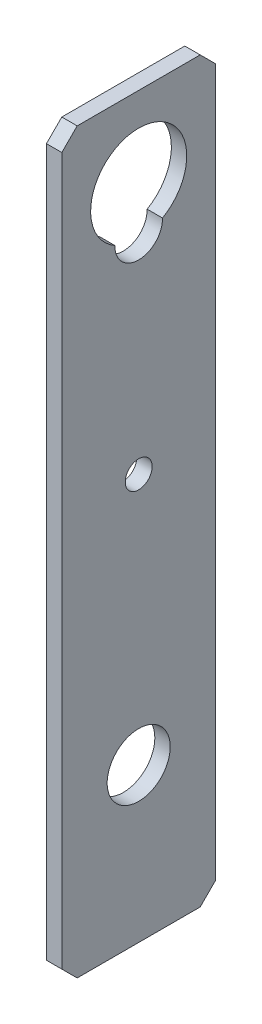
SolidWorks part; units mm, degrees
ref_plane "Front Plane" through (0, 0, 0) normal (0, 0, 1) x (1, 0, 0)
ref_plane "Top Plane" through (0, 0, 0) normal (0, 1, 0) x (1, 0, 0)
ref_plane "Right Plane" through (0, 0, 0) normal (1, 0, 0) x (0, 0, -1)
sketch "Sketch1" plane through (0, 0, 0) normal (1, 0, 0) x (0, 0, -1)
  line L1 (-10, -48) -> (10, -48)
  line L2 (-10, -48) -> (-10, 48)
  line L3 (-10, 48) -> (10, 48)
  line L4 (10, -48) -> (10, 48)
  line L5 (-10, -48) -> (10, 48) construction
  line L6 (-10, 48) -> (10, -48) construction
  point P0 (0, 0)
  dimension "D1" = 96
  dimension "D2" = 20
extrude "Boss-Extrude2" add sketch "Sketch1" along normal blind 2
sketch "Sketch3" plane through (2, 0, 0) normal (1, 0, 0) x (0, 0, -1)
  line L0 (-10, -48) -> (10, -48) construction
  line L1 (10, 48) -> (-10, 48) construction
  circle A0 centre (0, 4.75) radius 1.75
  arc A1 (3.0992, 32.0725) -> (-3.0992, 32.0725) centre (0, 37.5) ccw
  circle A2 centre (0, -28) radius 4.1
  arc A3 (-3.0992, 32.0725) -> (3.0992, 32.0725) centre (0, 32) ccw
  dimension "D1" = 8.2
  dimension "D2" = 3.5
  dimension "D3" = 6.25
  dimension "D4" = 32.75
  dimension "D7" = 5.5
  dimension "D8" = 6.2
  dimension "D5" = 20
  dimension "D6" = 10.5
extrude "Cut-Extrude1" cut sketch "Sketch3" against normal through all
chamfer "Chamfer1" distance 2 angle 45 4 edges at (1, -48, 10) (1, -48, -10) (1, 48, -10) (1, 48, 10)
